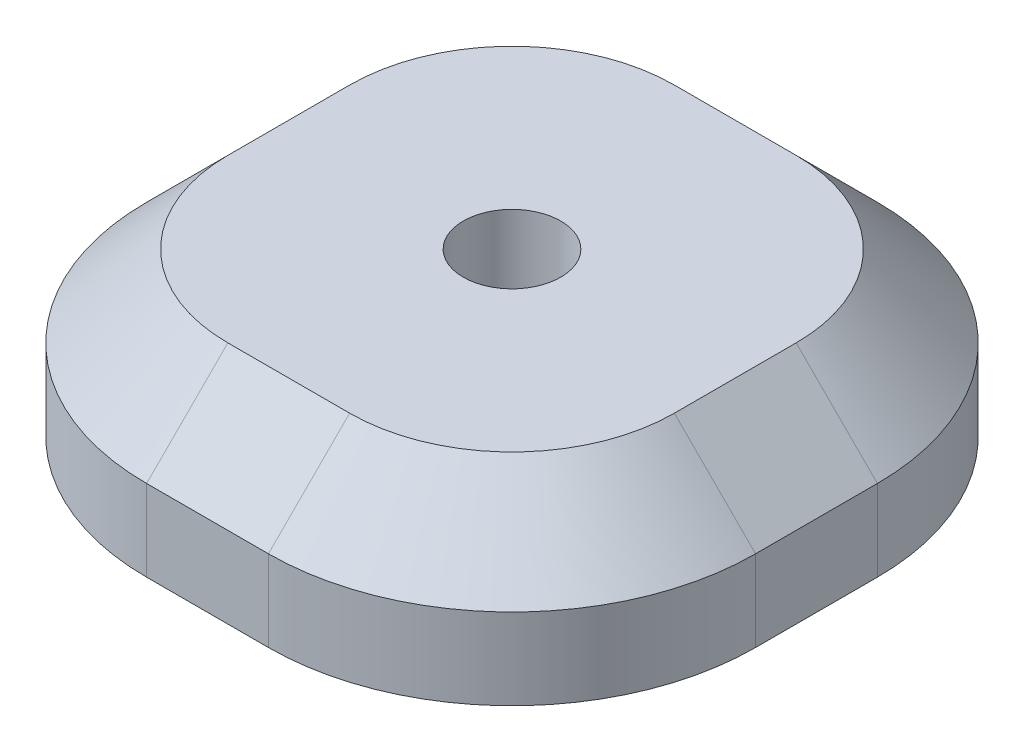
SolidWorks part; units mm, degrees
ref_plane "前基準面" through (0, 0, 0) normal (0, 0, 1) x (1, 0, 0)
ref_plane "上基準面" through (0, 0, 0) normal (0, 1, 0) x (1, 0, 0)
ref_plane "右基準面" through (0, 0, 0) normal (1, 0, 0) x (0, 0, -1)
ref_plane "平面1"
sketch "草圖1" plane through (0, 0, 0) normal (0, 1, 0) x (-1, 0, 0)
  line L0 (37.5, -37.5) -> (-37.5, -37.5)
  line L1 (-37.5, -37.5) -> (-37.5, 37.5)
  line L2 (-37.5, 37.5) -> (37.5, 37.5)
  line L3 (37.5, 37.5) -> (37.5, -37.5)
  dimension "D1" = 75
  dimension "D2" = 75
extrude "擠出1" add sketch "草圖1" along normal blind 20
fillet "圓角1" radius 30 4 edges at (37.5, 10, -37.5) (-37.5, 10, 37.5) (-37.5, 10, -37.5) (37.5, 10, 37.5)
chamfer "倒角1" distance 10 distance2 10 8 edges at (28.7132, 20, 28.7132) (0, 20, 37.5) (-28.7132, 20, 28.7132) (-37.5, 20, 0) (-28.7132, 20, -28.7132) (0, 20, -37.5) (28.7132, 20, -28.7132) (37.5, 20, 0)
hole_wizard "孔1" positions "草圖3" profile "草圖2" legacy
sketch "草圖3" plane through (0, 0, 0) normal (0, -1, 0) x (-1, 0, 0)
  point P1 (12.5, -12.5)
  point P2 (-12.5, -12.5)
  point P3 (-12.5, 12.5)
  point P4 (12.5, 12.5)
sketch "草圖2" plane through (-12.5, 0, 12.5) normal (1, 0, 0) x (0, 0, -1)
  line L0 (0, 0) -> (0, 13.6052)
  line L1 (0, 13.6052) -> (6, 10)
  line L2 (6, 10) -> (6, 0)
  line L4 (6, 0) -> (0, 0)
  line L6 (0, 13.6052) -> (-6, 10) construction
  line L7 (0, -4.2442) -> (0, 117.3081) construction
  dimension "直徑" = 12
  dimension "深度" = 10
  dimension "導頭角度" = 118
hole_wizard "孔2" positions "草圖5" profile "草圖4" legacy
sketch "草圖5" plane through (0, 20, 0) normal (0, 1, 0) x (1, 0, 0)
  point P1 (0, 0)
sketch "草圖4" plane through (0, 20, 0) normal (1, 0, 0) x (0, 0, 1)
  line L0 (0, 0) -> (0, 13.6052)
  line L1 (0, 13.6052) -> (6, 10)
  line L2 (6, 10) -> (6, 0)
  line L4 (6, 0) -> (0, 0)
  line L6 (0, 13.6052) -> (-6, 10) construction
  line L7 (0, -4.2442) -> (0, 117.3081) construction
  dimension "直徑" = 12
  dimension "深度" = 10
  dimension "導頭角度" = 118
